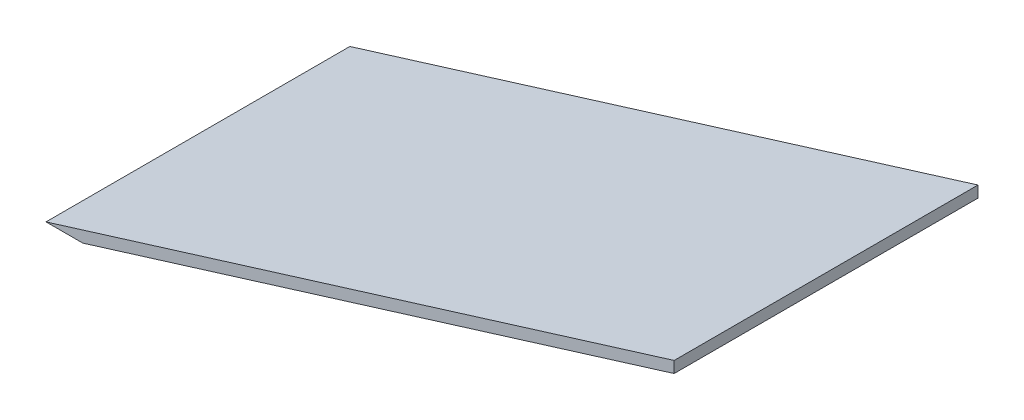
SolidWorks part; units mm, degrees
ref_plane "Front Plane" through (0, 0, 0) normal (0, 0, 1) x (1, 0, 0)
ref_plane "Top Plane" through (0, 0, 0) normal (0, 1, 0) x (1, 0, 0)
ref_plane "Right Plane" through (0, 0, 0) normal (1, 0, 0) x (0, 0, -1)
sketch "Sketch1" plane through (0, 0, 0) normal (0, 0, 1) x (1, 0, 0)
  line L0 (0, 0) -> (1013, 0) construction
  line L1 (1013, 0) -> (1013, 313) construction
  line L2 (0, 0) -> (1013, 313)
  line L3 (59.2794, 0) -> (1013, 294.6837)
  line L4 (59.2794, 0) -> (0, 0)
  line L5 (1013, 294.6837) -> (1013, 313)
  line L6 (1013, 294.6837) -> (1007.8338, 311.4037) construction
  line L7 (59.2794, 0) -> (54.1131, 16.7201) construction
  dimension "D1" = 1013
  dimension "D2" = 313
  dimension "D3" = 17.5
  dimension "D4" = 72.83
  dimension "D5" = 17.17
extrude "Boss-Extrude1" add sketch "Sketch1" along normal blind 490
